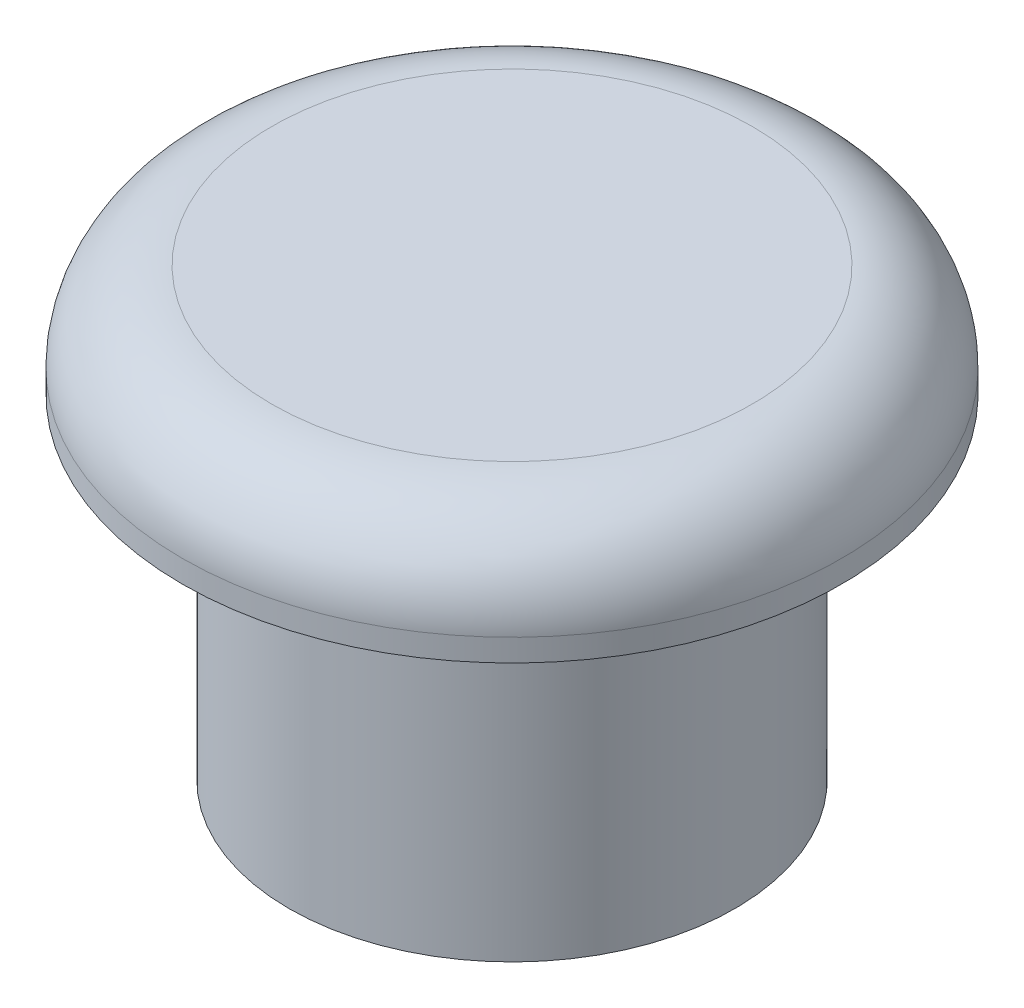
SolidWorks part; units mm, degrees
material "Cast Carbon Steel"
ref_plane "Front Plane" through (0, 0, 0) normal (0, 0, 1) x (1, 0, 0)
ref_plane "Top Plane" through (0, 0, 0) normal (0, 1, 0) x (1, 0, 0)
ref_plane "Right Plane" through (0, 0, 0) normal (1, 0, 0) x (0, 0, -1)
sketch "Sketch1" plane through (0, 0, 0) normal (0, 1, 0) x (1, 0, 0)
  circle A0 centre (0, 0) radius 2
extrude "Boss-Extrude1" add sketch "Sketch1" along normal blind 3
sketch "Sketch2" plane through (0, 3, 0) normal (0, 1, 0) x (1, 0, 0)
  circle A0 centre (0, 0) radius 2.9573
extrude "Boss-Extrude2" add sketch "Sketch2" along normal blind 1
fillet "Fillet1" radius 0.8
